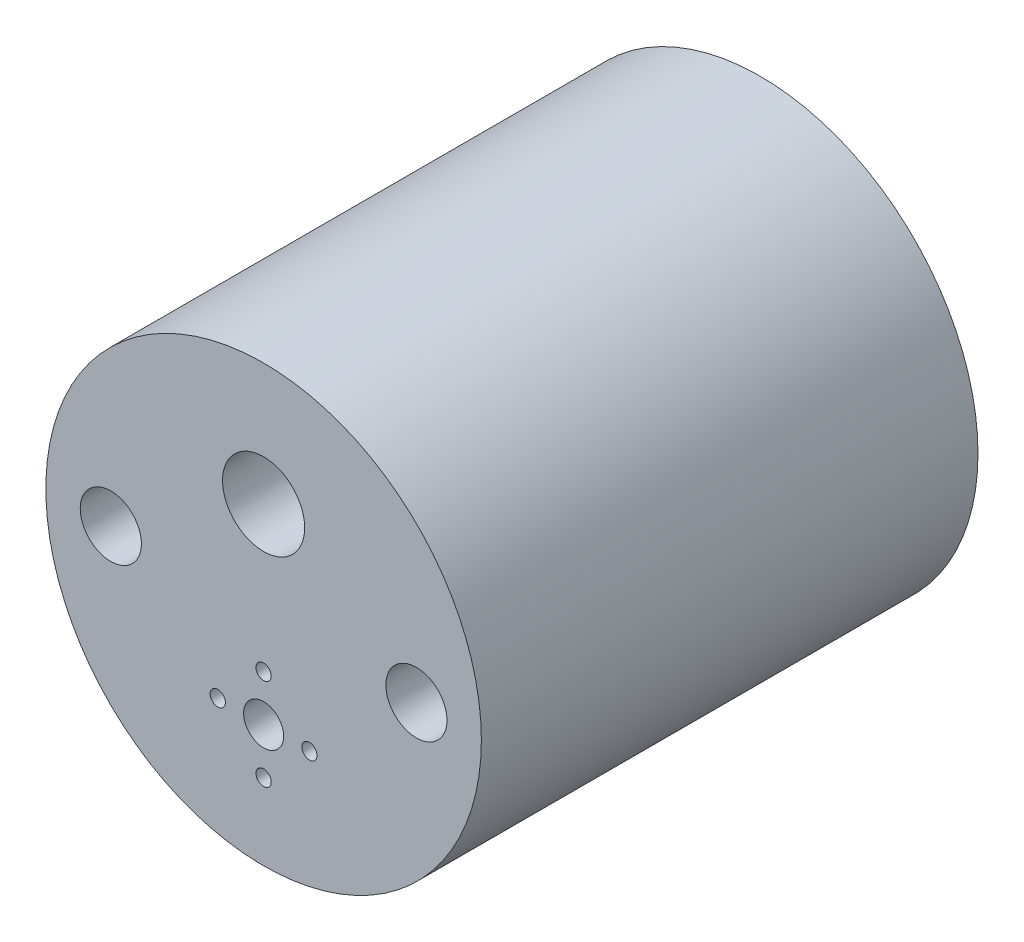
SolidWorks part; units mm, degrees
ref_plane "Front Plane" through (0, 0, 0) normal (0, 0, 1) x (1, 0, 0)
ref_plane "Top Plane" through (0, 0, 0) normal (0, 1, 0) x (1, 0, 0)
ref_plane "Right Plane" through (0, 0, 0) normal (1, 0, 0) x (0, 0, -1)
sketch "Sketch1" plane through (0, 0, 0) normal (0, 0, 1) x (1, 0, 0)
  circle A0 centre (12, 0) radius 2
  circle A1 centre (0, 25) radius 60 construction
  circle A2 centre (0, 25) radius 57
  circle A3 centre (0, -12) radius 2
  circle A4 centre (-12, 0) radius 2
  circle A11 centre (0, 0) radius 5.25
  circle A12 centre (0, 12) radius 2
  circle A14 centre (0, 50) radius 10.75
  dimension "D1" = 114
  dimension "D2" = 21.5
  dimension "D3" = 10.5
  dimension "D4" = 4
  dimension "D6" = 12
  dimension "D5" = 0
  dimension "D7" = 4
  dimension "D8" = 12
  dimension "D9" = 24
extrude "Boss-Extrude1" add sketch "Sketch1" against normal blind 20
sketch "Sketch2" plane through (0, 0, 0) normal (0, 0, 1) x (1, 0, 0)
  circle A1 centre (0, 25) radius 57
  circle A2 centre (0, 25) radius 57
  circle A3 centre (0, 25) radius 54
  dimension "D2" = 3
  dimension "D1" = 0
extrude "Boss-Extrude2" add sketch "Sketch2" against normal blind 130
sketch "Sketch3" plane through (0, 0, 0) normal (0, 0, 1) x (1, 0, 0)
  circle A0 centre (40, 25) radius 8
  circle A1 centre (0, 25) radius 57 construction
  point P2 (0, 25)
  dimension "D1" = 16
  dimension "D2" = 40
  dimension "D3" = 0
extrude "Cut-Extrude1" cut sketch "Sketch3" against normal blind 19.5
sketch "Sketch4" plane through (0, 0, 0) normal (0, 0, 1) x (1, 0, 0)
  circle A0 centre (40, 25) radius 5
  circle A1 centre (40, 25) radius 8 construction
  dimension "D1" = 10
sketch "Sketch5" plane through (0, 0, -20) normal (0, 0, -1) x (-1, 0, 0)
  circle A0 centre (-40, 25) radius 12
  circle A1 centre (-40, 25) radius 8 construction
  dimension "D1" = 24
extrude "Cut-Extrude3" cut sketch "Sketch5" against normal blind 6.05
mirror "Mirror1" about plane through (0, 0, 0) normal (1, 0, 0) of "Cut-Extrude3", "Cut-Extrude1"
